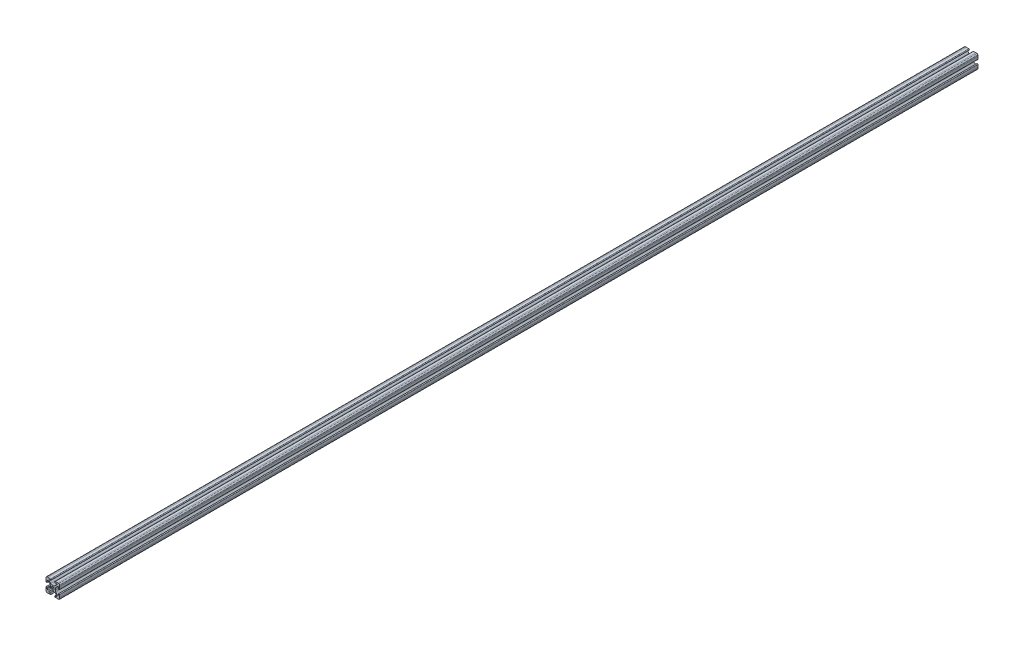
SolidWorks part; units mm, degrees
ref_plane "Front Plane" through (0, 0, 0) normal (0, 0, 1) x (1, 0, 0)
ref_plane "Top Plane" through (0, 0, 0) normal (0, 1, 0) x (1, 0, 0)
ref_plane "Right Plane" through (0, 0, 0) normal (1, 0, 0) x (0, 0, -1)
sketch "Model" plane through (0, 0, 0) normal (0, 0, 1) x (1, 0, 0)
  line L38 (50.6495, 75.4336) -> (50.2699, 75.4336)
  line L39 (50.2699, 75.4336) -> (50.2699, 75.8133)
  line L40 (50.66, 72.9999) -> (53.7746, 72.9999)
  line L41 (56.0196, 72.0699) -> (59.2642, 68.8254)
  line L42 (58.5103, 67.0916) -> (56.5725, 67.1592)
  line L43 (56.498, 65.0269) -> (60.6773, 64.881)
  line L44 (60.6773, 64.881) -> (62.7107, 64.881)
  line L45 (64.7173, 66.8876) -> (64.7173, 68.921)
  line L46 (64.7173, 68.921) -> (64.5713, 73.1002)
  line L47 (62.439, 73.0257) -> (62.5067, 71.0879)
  line L48 (60.7729, 70.334) -> (57.5283, 73.5786)
  line L49 (56.5984, 75.8237) -> (56.5984, 78.9383)
  line L50 (57.5283, 81.1833) -> (60.7729, 84.4279)
  line L51 (62.5067, 83.674) -> (62.439, 81.7362)
  line L52 (64.5713, 81.6617) -> (64.7173, 85.841)
  line L53 (64.7173, 85.841) -> (64.7173, 87.8744)
  line L54 (62.7107, 89.881) -> (60.6773, 89.881)
  line L55 (60.6773, 89.881) -> (56.498, 89.735)
  line L56 (56.5725, 87.6027) -> (58.5103, 87.6704)
  line L57 (59.2642, 85.9366) -> (56.0196, 82.692)
  line L58 (53.7746, 81.7621) -> (50.66, 81.7621)
  line L59 (48.4149, 82.692) -> (45.1703, 85.9366)
  line L60 (45.9242, 87.6704) -> (47.862, 87.6027)
  line L61 (47.9365, 89.735) -> (43.7573, 89.881)
  line L62 (43.7573, 89.881) -> (41.7239, 89.881)
  line L63 (39.7173, 87.8744) -> (39.7173, 85.841)
  line L64 (39.7173, 85.841) -> (39.8632, 81.6617)
  line L65 (41.9955, 81.7362) -> (41.9278, 83.674)
  line L66 (43.6616, 84.4279) -> (46.9062, 81.1833)
  line L67 (47.8361, 78.9383) -> (47.8361, 75.8237)
  line L68 (46.9062, 73.5786) -> (43.6616, 70.334)
  line L69 (41.9278, 71.0879) -> (41.9955, 73.0257)
  line L70 (39.8632, 73.1002) -> (39.7173, 68.921)
  line L71 (39.7173, 68.921) -> (39.7173, 66.8876)
  line L72 (41.7239, 64.881) -> (43.7573, 64.881)
  line L73 (43.7573, 64.881) -> (47.9365, 65.0269)
  line L74 (47.862, 67.1592) -> (45.9242, 67.0916)
  line L75 (45.1703, 68.8254) -> (48.4149, 72.0699)
  arc A29 (50.6495, 75.4336) -> (50.2699, 75.8133) centre (52.2173, 77.381) ccw
  arc A30 (56.0196, 72.0699) -> (53.7746, 72.9999) centre (53.7746, 69.8249) ccw
  arc A31 (58.5103, 67.0916) -> (59.2642, 68.8254) centre (58.5458, 68.1069) ccw
  arc A32 (56.5725, 67.1592) -> (56.498, 65.0269) centre (56.5353, 66.0931) ccw
  arc A33 (62.7107, 64.881) -> (64.7173, 66.8876) centre (62.7107, 66.8876) ccw
  arc A34 (64.5713, 73.1002) -> (62.439, 73.0257) centre (63.5052, 73.063) ccw
  arc A35 (60.7729, 70.334) -> (62.5067, 71.0879) centre (61.4913, 71.0525) ccw
  arc A36 (56.5984, 75.8237) -> (57.5283, 73.5786) centre (59.7734, 75.8237) ccw
  arc A37 (57.5283, 81.1833) -> (56.5984, 78.9383) centre (59.7734, 78.9383) ccw
  arc A38 (62.5067, 83.674) -> (60.7729, 84.4279) centre (61.4913, 83.7095) ccw
  arc A39 (62.439, 81.7362) -> (64.5713, 81.6617) centre (63.5052, 81.699) ccw
  arc A40 (64.7173, 87.8744) -> (62.7107, 89.881) centre (62.7107, 87.8744) ccw
  arc A41 (56.498, 89.735) -> (56.5725, 87.6027) centre (56.5353, 88.6689) ccw
  arc A42 (59.2642, 85.9366) -> (58.5103, 87.6704) centre (58.5458, 86.655) ccw
  arc A43 (53.7746, 81.7621) -> (56.0196, 82.692) centre (53.7746, 84.9371) ccw
  arc A44 (48.4149, 82.692) -> (50.66, 81.7621) centre (50.66, 84.9371) ccw
  arc A45 (45.9242, 87.6704) -> (45.1703, 85.9366) centre (45.8887, 86.655) ccw
  arc A46 (47.862, 87.6027) -> (47.9365, 89.735) centre (47.8993, 88.6689) ccw
  arc A47 (41.7239, 89.881) -> (39.7173, 87.8744) centre (41.7239, 87.8744) ccw
  arc A48 (39.8632, 81.6617) -> (41.9955, 81.7362) centre (40.9293, 81.699) ccw
  arc A49 (43.6616, 84.4279) -> (41.9278, 83.674) centre (42.9432, 83.7095) ccw
  arc A50 (47.8361, 78.9383) -> (46.9062, 81.1833) centre (44.6611, 78.9383) ccw
  arc A51 (46.9062, 73.5786) -> (47.8361, 75.8237) centre (44.6611, 75.8237) ccw
  arc A52 (41.9278, 71.0879) -> (43.6616, 70.334) centre (42.9432, 71.0525) ccw
  arc A53 (41.9955, 73.0257) -> (39.8632, 73.1002) centre (40.9293, 73.063) ccw
  arc A54 (39.7173, 66.8876) -> (41.7239, 64.881) centre (41.7239, 66.8876) ccw
  arc A55 (47.9365, 65.0269) -> (47.862, 67.1592) centre (47.8993, 66.0931) ccw
  arc A56 (45.1703, 68.8254) -> (45.9242, 67.0916) centre (45.8887, 68.1069) ccw
  arc A57 (50.66, 72.9999) -> (48.4149, 72.0699) centre (50.66, 69.8249) ccw
extrude "Boss-Extrude1" add sketch "Model" along normal blind 1675.384
